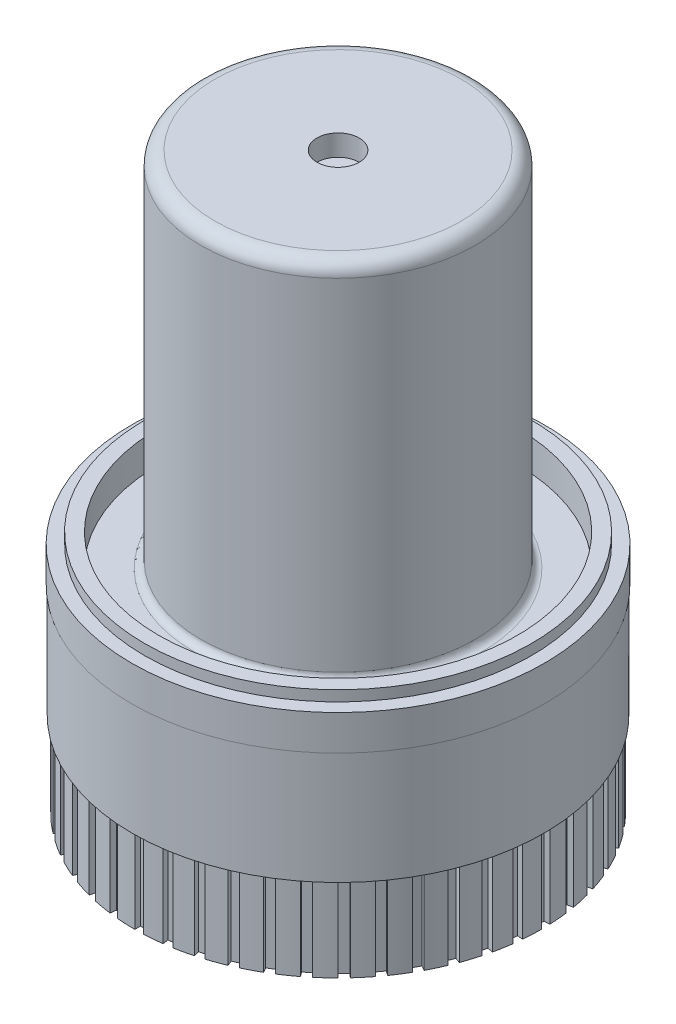
SolidWorks part; units mm, degrees
ref_plane "Front Plane" through (0, 0, 0) normal (0, 0, 1) x (1, 0, 0)
ref_plane "Top Plane" through (0, 0, 0) normal (0, 1, 0) x (1, 0, 0)
ref_plane "Right Plane" through (0, 0, 0) normal (1, 0, 0) x (0, 0, -1)
sketch "Sketch1" plane through (0, 0, 0) normal (0, 1, 0) x (1, 0, 0)
  circle A0 centre (0, 0) radius 29.25
  dimension "D1" = 58.5
extrude "Boss-Extrude1" add sketch "Sketch1" along normal blind 16
sketch "Sketch2" plane through (0, 16, 0) normal (0, 1, 0) x (1, 0, 0)
  circle A0 centre (0, 0) radius 29.35
  dimension "D1" = 58.7
extrude "Boss-Extrude2" add sketch "Sketch2" along normal blind 5
sketch "Sketch3" plane through (0, 21, 0) normal (0, 1, 0) x (1, 0, 0)
  circle A0 centre (0, 0) radius 27.5
  dimension "D1" = 55
extrude "Boss-Extrude3" add sketch "Sketch3" along normal blind 1.5
sketch "Sketch4" plane through (0, 0, 0) normal (0, -1, 0) x (1, 0, 0)
  circle A0 centre (0, 0) radius 28.9
  dimension "D1" = 57.8
extrude "Boss-Extrude4" add sketch "Sketch4" along normal blind 12
sketch "Sketch6" plane through (0, -12, 0) normal (0, -1, 0) x (1, 0, 0)
  line L0 (0, 0) -> (0, 28.9)
  line L2 (1.2339, 28.8736) -> (0, 0)
  line L3 (0, 28.0998) -> (1.1997, 28.0744)
  circle A0 centre (0, 0) radius 28.9 construction
  circle A1 centre (0, 0) radius 28.9
  circle M3 centre (0, 0) radius 28.9
  dimension "D1" = 1.2
  dimension "D2" = 0.8
  dimension "D3" = 0.8
extrude "Cut-Extrude1" cut sketch "Sketch6" against normal blind 12 contours L0 L3 L2 M3
pattern_circular "CirPattern1" count 48 over 360 about axis through (0, 0, 0) along (0, 1, 0) of "Cut-Extrude1"
sketch "Sketch7" plane through (0, 22.5, 0) normal (0, 1, 0) x (1, 0, 0)
  circle A0 centre (0, 0) radius 25.5
  dimension "D1" = 51
extrude "Cut-Extrude2" cut sketch "Sketch7" against normal blind 4.5
sketch "Sketch8" plane through (0, 18, 0) normal (0, 1, 0) x (1, 0, 0)
  circle A0 centre (0, 0) radius 19.5
  dimension "D1" = 39
extrude "Boss-Extrude6" add sketch "Sketch8" along normal blind 51.5
fillet "Fillet1" radius 2 1 edges at (0, 69.5, 19.5)
sketch "Sketch9" plane through (0, 69.5, 0) normal (0, 1, 0) x (1, 0, 0)
  circle A0 centre (0, 0) radius 3
  dimension "D1" = 6
extrude "Cut-Extrude3" cut sketch "Sketch9" against normal blind 3
fillet "Fillet2" radius 1 1 edges at (0, 18, 19.5)
